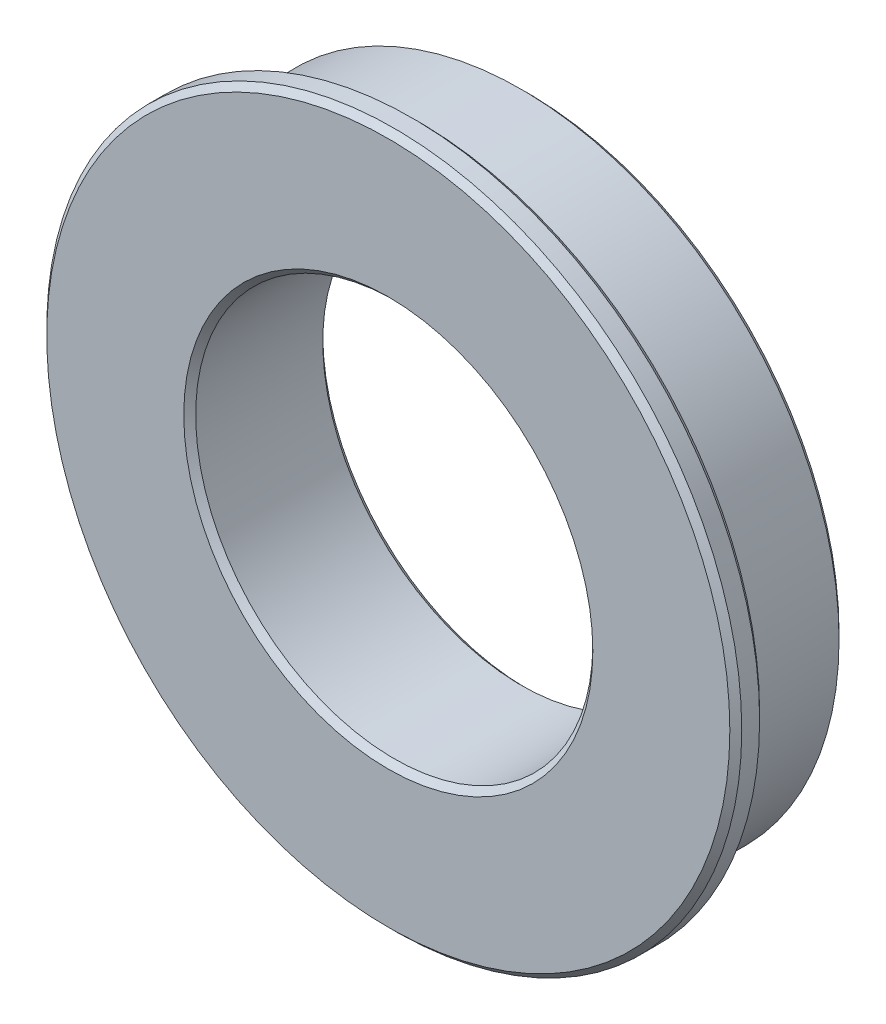
SolidWorks part; units mm, degrees
ref_plane "前视基准面" through (0, 0, 0) normal (0, 0, 1) x (1, 0, 0)
ref_plane "上视基准面" through (0, 0, 0) normal (0, 1, 0) x (1, 0, 0)
ref_plane "右视基准面" through (0, 0, 0) normal (1, 0, 0) x (0, 0, -1)
sketch "草图1" plane through (0, 0, 0) normal (0, 0, 1) x (1, 0, 0)
  circle A0 centre (0, 0) radius 16
  circle A1 centre (0, 0) radius 10
  dimension "D1" = 20
  dimension "D2" = 32
extrude "凸台-拉伸1" add sketch "草图1" along normal mid plane 7
sketch "草图2" plane through (0, 0, 3.5) normal (0, 0, 1) x (1, 0, 0)
  circle A0 centre (0, 0) radius 17.5
  circle A1 centre (0, 0) radius 10 construction
  circle A2 centre (0, 0) radius 10
  dimension "D1" = 35
extrude "凸台-拉伸2" add sketch "草图2" against normal blind 1.5
chamfer "倒角1" distance 0.3 angle 45 5 edges at (10, 0, 3.5) (17.5, 0, 2) (17.5, 0, 3.5) (10, 0, -3.5) (16, 0, -3.5)
